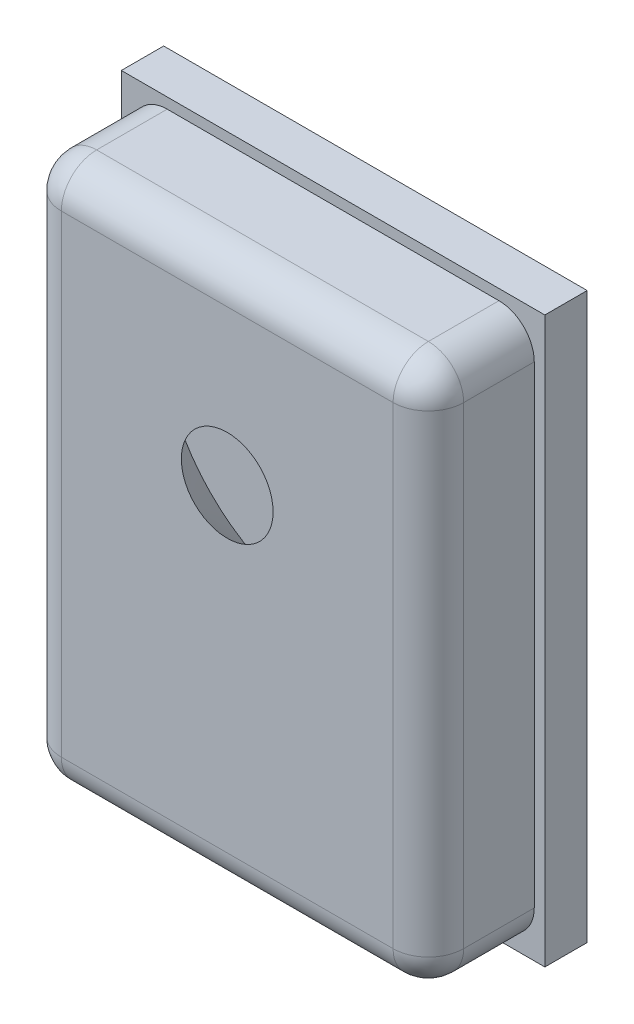
SolidWorks part; units mm, degrees
ref_plane "Спереди" through (0, 0, 0) normal (0, 0, 1) x (1, 0, 0)
ref_plane "Сверху" through (0, 0, 0) normal (0, 1, 0) x (1, 0, 0)
ref_plane "Справа" through (0, 0, 0) normal (1, 0, 0) x (0, 0, -1)
sketch "Эскиз1" plane through (0, 0, 0) normal (0, 0, 1) x (1, 0, 0)
  line L1 (-1.5, 2) -> (1.5, 2)
  line L2 (-1.5, 2) -> (-1.5, -2)
  line L3 (-1.5, -2) -> (1.5, -2)
  line L4 (1.5, 2) -> (1.5, -2)
  line L5 (-1.5, 2) -> (1.5, -2) construction
  line L6 (-1.5, -2) -> (1.5, 2) construction
  point P0 (0, 0)
  dimension "D1" = 4
  dimension "D2" = 3
extrude "Бобышка-Вытянуть1" add sketch "Эскиз1" along normal blind 0.3
sketch "Эскиз2" plane through (0, 0, 0.3) normal (0, 0, 1) x (1, 0, 0)
  line L1 (-1.175, 1.925) -> (1.175, 1.925)
  line L2 (-1.425, 1.675) -> (-1.425, -1.675)
  line L3 (-1.175, -1.925) -> (1.175, -1.925)
  line L4 (1.425, 1.675) -> (1.425, -1.675)
  line L5 (-1.425, 1.925) -> (1.425, -1.925) construction
  line L6 (-1.425, -1.925) -> (1.425, 1.925) construction
  arc A0 (-1.425, -1.675) -> (-1.175, -1.925) centre (-1.175, -1.675) ccw
  arc A1 (1.175, -1.925) -> (1.425, -1.675) centre (1.175, -1.675) ccw
  arc A2 (1.425, 1.675) -> (1.175, 1.925) centre (1.175, 1.675) ccw
  arc A3 (-1.425, 1.675) -> (-1.175, 1.925) centre (-1.175, 1.675) cw
  point P0 (0, 0)
  dimension "D3" = 0.25
  dimension "D1" = 2.85
  dimension "D2" = 3.85
extrude "Бобышка-Вытянуть2" add sketch "Эскиз2" along normal blind 0.75
fillet "Скругление1" radius 0.25 8 edges at (-1.425, 0, 1.05) (-1.3518, 1.8518, 1.05) (0, 1.925, 1.05) (1.3518, 1.8518, 1.05) (1.425, 0, 1.05) (1.3518, -1.8518, 1.05) (0, -1.925, 1.05) (-1.3518, -1.8518, 1.05)
sketch "Эскиз3" plane through (0, 0, 1.05) normal (0, 0, 1) x (1, 0, 0)
  line L0 (-1.5, 2) -> (-1.5, -2) construction
  line L1 (1.5, 2) -> (-1.5, 2) construction
  circle A0 centre (0, 0.58) radius 0.325
  point P6 (0, 2)
  dimension "D3" = 0.65
  dimension "D1" = 1.5
  dimension "D2" = 1.42
extrude "Вырез-Вытянуть1" cut sketch "Эскиз3" against normal blind 0.75 draft 50 draft outward yes
sketch "Эскиз4" plane through (0, 0, 0) normal (0, 0, -1) x (-1, 0, 0)
  line L0 (-1.5, -2) -> (-1.5, 2) construction
  line L1 (-1.4, -1.2) -> (-0.5, -1.2)
  line L2 (-1.4, -1.2) -> (-1.4, -1.8)
  line L3 (-1.4, -1.8) -> (-0.5, -1.8)
  line L4 (-0.5, -1.2) -> (-0.5, -1.8)
  line L5 (-1.4, -1.2) -> (-0.5, -1.8) construction
  line L6 (-1.4, -1.8) -> (-0.5, -1.2) construction
  line L7 (1.5, -2) -> (-1.5, -2) construction
  line L8 (0.5, -1.2) -> (0.5, -1.8)
  line L9 (0.5, -1.2) -> (1.4, -1.2)
  line L10 (1.4, -1.2) -> (1.4, -1.8)
  line L11 (0.5, -1.8) -> (1.4, -1.8)
  line L12 (0.5, -0.2) -> (0.5, -0.8)
  line L13 (0.5, -0.2) -> (1.4, -0.2)
  line L14 (1.4, -0.2) -> (1.4, -0.8)
  line L15 (0.5, -0.8) -> (1.4, -0.8)
  line L16 (0.5, 0.8) -> (0.5, 0.2)
  line L17 (0.5, 0.8) -> (1.4, 0.8)
  line L18 (1.4, 0.8) -> (1.4, 0.2)
  line L19 (0.5, 0.2) -> (1.4, 0.2)
  line L20 (0.5, 1.8) -> (0.5, 1.2)
  line L21 (0.5, 1.8) -> (1.4, 1.8)
  line L22 (1.4, 1.8) -> (1.4, 1.2)
  line L23 (0.5, 1.2) -> (1.4, 1.2)
  line L24 (-1.4, -0.2) -> (-1.4, -0.8)
  line L25 (-1.4, -0.2) -> (-0.5, -0.2)
  line L26 (-0.5, -0.2) -> (-0.5, -0.8)
  line L27 (-1.4, -0.8) -> (-0.5, -0.8)
  line L28 (-1.4, 0.8) -> (-1.4, 0.2)
  line L29 (-1.4, 0.8) -> (-0.5, 0.8)
  line L30 (-0.5, 0.8) -> (-0.5, 0.2)
  line L31 (-1.4, 0.2) -> (-0.5, 0.2)
  line L32 (-1.4, 1.8) -> (-1.4, 1.2)
  line L33 (-1.4, 1.8) -> (-0.5, 1.8)
  line L34 (-0.5, 1.8) -> (-0.5, 1.2)
  line L35 (-1.4, 1.2) -> (-0.5, 1.2)
  point P0 (-0.95, -1.5)
  point P10 (-1.4, 1.5)
  dimension "D1" = 0.6
  dimension "D2" = 0.9
  dimension "D3" = 0.1
  dimension "D4" = 0.2
  dimension "D7" = 1
  dimension "D8" = 0.4
  dimension "D9" = 0.1
  dimension "D5" = 2
  dimension "D6" = 4
extrude "Бобышка-Вытянуть3" add sketch "Эскиз4" along normal blind 0.05
